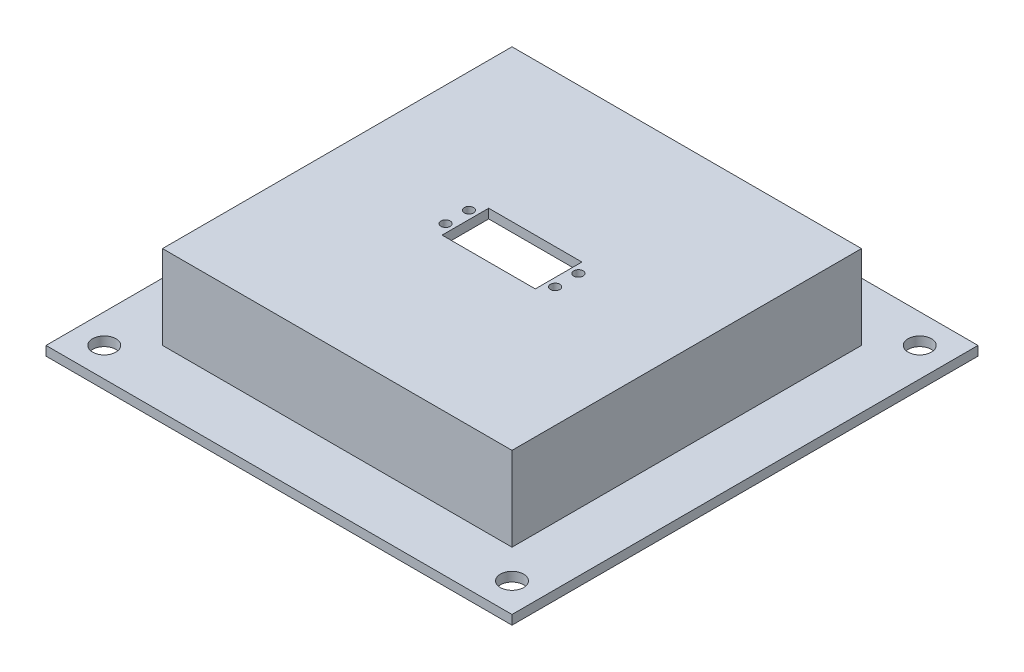
SolidWorks part; units mm, degrees
ref_plane "Ön Düzlem" through (0, 0, 0) normal (0, 0, 1) x (1, 0, 0)
ref_plane "Üst Düzlem" through (0, 0, 0) normal (0, 1, 0) x (1, 0, 0)
ref_plane "Sağ Düzlem" through (0, 0, 0) normal (1, 0, 0) x (0, 0, -1)
sketch "Çizim1" plane through (0, 0, 0) normal (0, 1, 0) x (1, 0, 0)
  line L1 (0, 0) -> (-150, 0)
  line L2 (0, 0) -> (0, 150)
  line L3 (0, 150) -> (-150, 150)
  line L4 (-150, 0) -> (-150, 150)
  dimension "D1" = 150
  dimension "D2" = 150
extrude "Yükseklik-Ekstrüzyon1" add sketch "Çizim1" along normal blind 40
shell "İç Boşaltma1" thickness 4
sketch "Çizim2" plane through (0, 0, 0) normal (0, -1, 0) x (1, 0, 0)
  line L1 (0, -150) -> (-150, -150)
  line L2 (0, -150) -> (0, 0)
  line L3 (0, 0) -> (-150, 0)
  line L4 (-150, -150) -> (-150, 0)
  line L5 (25, -175) -> (-175, -175)
  line L6 (25, -175) -> (25, 25)
  line L7 (25, 25) -> (-175, 25)
  line L8 (-175, -175) -> (-175, 25)
  dimension "D1" = 200
  dimension "D2" = 200
  dimension "D3" = 25
  dimension "D4" = 25
extrude "Yükseklik-Ekstrüzyon2" add sketch "Çizim2" against normal blind 4
sketch "Çizim3" plane through (0, 4, 0) normal (0, 1, 0) x (1, 0, 0)
  circle A0 centre (12.5, 162.5) radius 5
  circle A1 centre (12.5, -12.5) radius 5
  circle A2 centre (-162.5, -12.5) radius 5
  circle A3 centre (-162.5, 162.5) radius 5
  dimension "D1" = 10
extrude "Kes-Ekstrüzyon1" cut sketch "Çizim3" against normal up to next
sketch "Çizim4" plane through (0, 40, 0) normal (0, 1, 0) x (1, 0, 0)
  line L0 (0, 150) -> (-150, 150) construction
  line L1 (-95, 85) -> (-55, 85)
  line L2 (-95, 85) -> (-95, 65)
  line L3 (-95, 65) -> (-55, 65)
  line L4 (-55, 85) -> (-55, 65)
  line L5 (-150, 150) -> (-150, 0) construction
  circle A0 centre (-51.5, 70) radius 2
  circle A1 centre (-51.5, 80) radius 2
  circle A2 centre (-98.5, 80) radius 2
  circle A3 centre (-98.5, 70) radius 2
  dimension "D7" = 4
  dimension "D1" = 20
  dimension "D2" = 40
  dimension "D3" = 65
  dimension "D4" = 55
extrude "Kes-Ekstrüzyon2" cut sketch "Çizim4" against normal up to next
